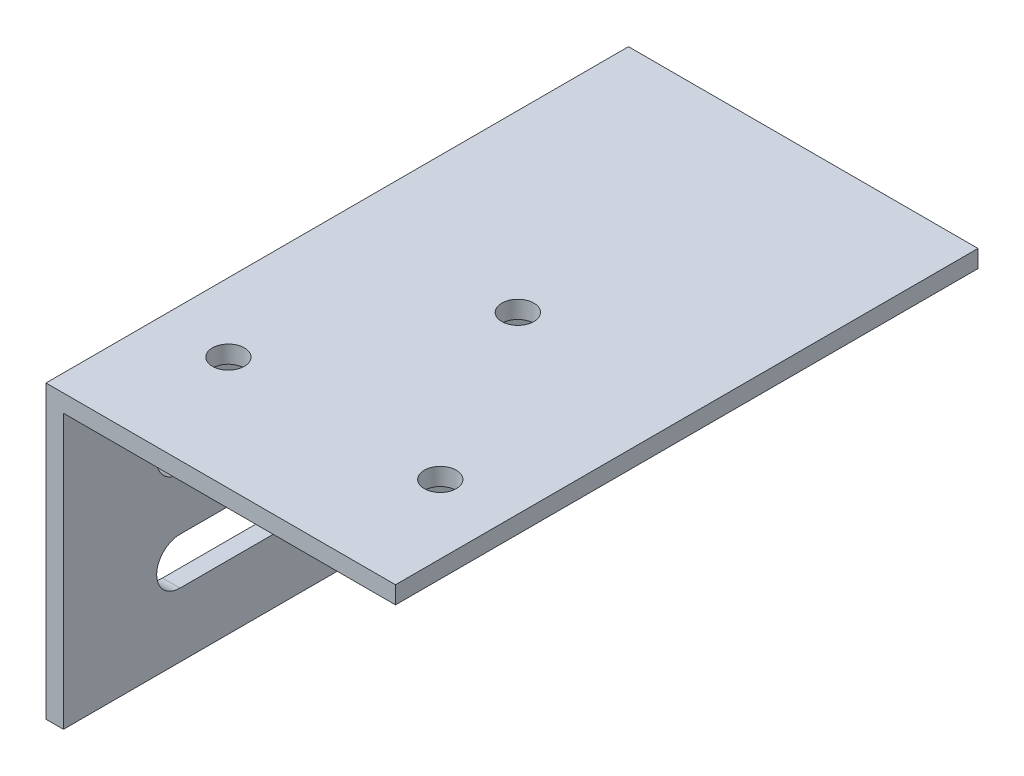
SolidWorks part; units mm, degrees
material "1023 Carbon Steel Sheet (SS)"
ref_plane "Front Plane" through (0, 0, 0) normal (0, 0, 1) x (1, 0, 0)
ref_plane "Top Plane" through (0, 0, 0) normal (0, 1, 0) x (1, 0, 0)
ref_plane "Right Plane" through (0, 0, 0) normal (1, 0, 0) x (0, 0, -1)
sketch "Sketch1" plane through (0, 0, 0) normal (0, 0, 1) x (1, 0, 0)
  line L0 (0, 0) -> (-60, 0)
  line L1 (-60, 0) -> (-60, -50)
  line L2 (-60, -50) -> (-57, -50)
  line L3 (-57, -50) -> (-57, -3)
  line L4 (-57, -3) -> (0, -3)
  line L5 (0, -3) -> (0, 0)
  dimension "D1" = 3
  dimension "D2" = 3
  dimension "D3" = 60
  dimension "D4" = 50
extrude "Boss-Extrude1" add sketch "Sketch1" along normal blind 100
sketch "Sketch2" plane through (0, 0, 0) normal (0, 1, 0) x (1, 0, 0)
  line L0 (-60, -100) -> (-60, 0) construction
  line L1 (0, -100) -> (-60, -100) construction
  line L2 (-30, -70) -> (4.1893, -70) construction
  line L3 (-30, -70) -> (1.8252, -88.3743) construction
  circle A0 centre (-30, -70) radius 21 construction
  circle A1 centre (-11.8135, -80.5) radius 2.75
  circle A2 centre (-48.1865, -80.5) radius 2.75
  circle A3 centre (-30, -49) radius 2.75
  dimension "D1" = 42
  dimension "D5" = 5.5
  dimension "D2" = 30
  dimension "D3" = 30
  dimension "D4" = 30
  dimension "D6" = 3
extrude "Cut-Extrude1" cut sketch "Sketch2" against normal blind 100
sketch "Sketch3" plane through (-57, 0, 0) normal (1, 0, 0) x (0, 0, -1)
  line L0 (-80, -18) -> (-20, -18) construction
  line L1 (-80, -14) -> (-20, -14)
  line L2 (-80, -22) -> (-20, -22)
  line L3 (0, -50) -> (0, -3) construction
  line L4 (-100, -3) -> (0, -3) construction
  line L5 (0, -26.5) -> (-100, -26.5) construction
  line L6 (-100, -50) -> (-100, -3) construction
  line L7 (-80, -35) -> (-20, -35) construction
  line L8 (-80, -39) -> (-20, -39)
  line L9 (-80, -31) -> (-20, -31)
  arc A0 (-80, -14) -> (-80, -22) centre (-80, -18) ccw
  arc A1 (-20, -22) -> (-20, -14) centre (-20, -18) ccw
  arc A2 (-80, -39) -> (-80, -31) centre (-80, -35) cw
  arc A3 (-20, -31) -> (-20, -39) centre (-20, -35) cw
  point P2 (-50, -18)
  point P17 (-50, -35)
  dimension "D3" = 4
  dimension "D1" = 60
  dimension "D2" = 50
  dimension "D4" = 15
extrude "Cut-Extrude2" cut sketch "Sketch3" against normal blind 100
